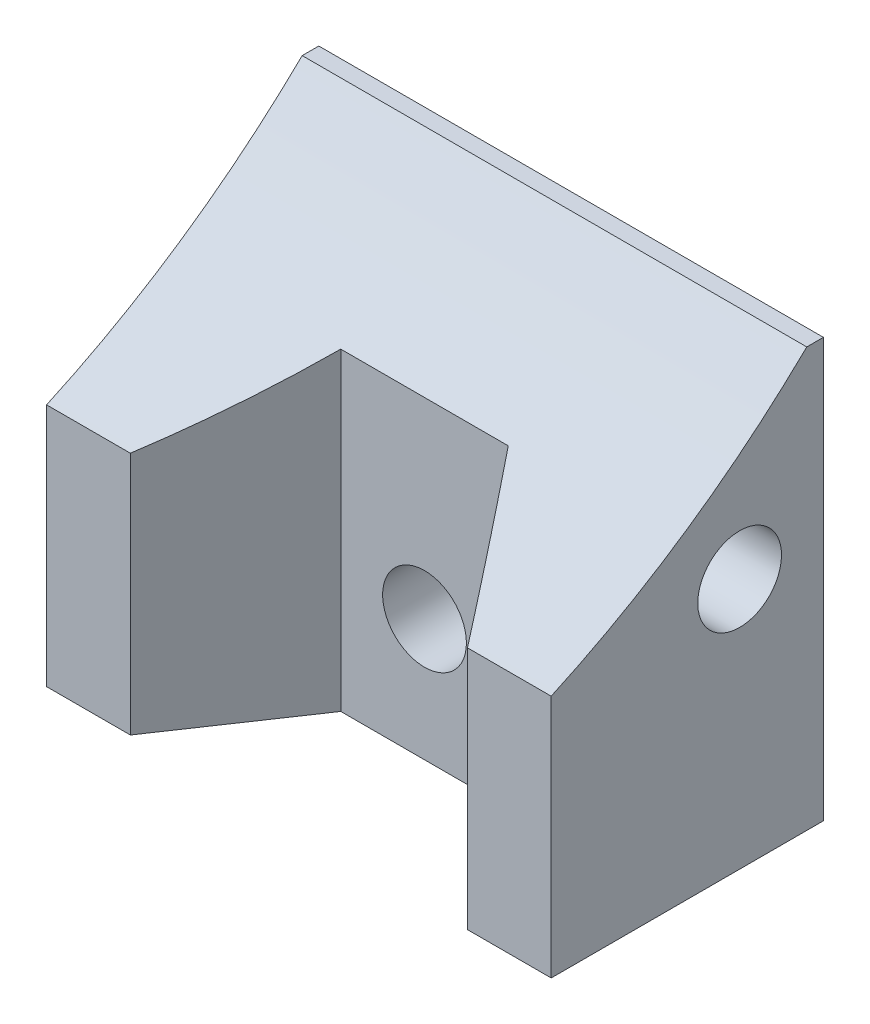
SolidWorks part; units mm, degrees
ref_plane "前视基准面" through (0, 0, 0) normal (0, 0, 1) x (1, 0, 0)
ref_plane "上视基准面" through (0, 0, 0) normal (0, 1, 0) x (1, 0, 0)
ref_plane "右视基准面" through (0, 0, 0) normal (1, 0, 0) x (0, 0, -1)
sketch "草图1" plane through (0, 0, 0) normal (0, 0, 1) x (1, 0, 0)
  line L2 (-12.05, 10) -> (12.05, 10)
  line L3 (-12.05, 10) -> (-12.05, -10)
  line L4 (-12.05, -10) -> (12.05, -10)
  line L8 (12.05, 10) -> (12.05, -10)
  line L9 (-12.05, 10) -> (12.05, -10) construction
  line L10 (-12.05, -10) -> (12.05, 10) construction
  point P0 (0, 0)
  dimension "D1" = 20
  dimension "D2" = 24.1
extrude "凸台-拉伸1" add sketch "草图1" along normal blind 13
sketch "草图3" plane through (12.05, 0, 0) normal (1, 0, 0) x (0, 0, -1)
  line L4 (0, -10) -> (0, 10)
  line L5 (0, 10) -> (-13, 10)
  line L6 (-13, 10) -> (-13, -10)
  line L7 (-13, -10) -> (0, -10)
  line L9 (-0.794, 10) -> (-13, 10)
  line L10 (-13, 10) -> (-13, 1.6572)
  arc A2 (-13, 1.6572) -> (-0.794, 10) centre (-30.8, 40.8) ccw
  point P0 (-30.8, 40.8)
  point P6 (5.5396, 51.9101)
  point P9 (12.2, 40.8)
  dimension "D1" = 0
extrude "切除-拉伸2" cut sketch "草图3" against normal through all
sketch "草图4" plane through (0, 0, 13) normal (0, 0, 1) x (1, 0, 0)
  line L0 (-12.05, -10) -> (12.05, 1.6572) construction
  line L2 (12.05, -10) -> (-12.05, 1.6572) construction
  line L3 (-12.05, 1.6572) -> (-12.05, -10) construction
  line L4 (-12.05, 1.6572) -> (12.05, 1.6572) construction
  circle A0 centre (0, -4.1714) radius 2
  dimension "D1" = 4
extrude "切除-拉伸3" cut sketch "草图4" against normal through all contours A0
sketch "草图5" plane through (0, -10, 0) normal (0, -1, 0) x (1, 0, 0)
  line L0 (0, 0) -> (0, 13) construction
  line L1 (-12.05, 0) -> (12.05, 0) construction
  line L2 (-12.05, 13) -> (12.05, 13) construction
  line L3 (-8.05, 13) -> (-4, 7)
  line L4 (-4, 7) -> (4, 7)
  line L5 (-8.05, 13) -> (8.05, 13)
  line L6 (0, 13) -> (0, 7)
  line L7 (-12.05, 13) -> (-12.05, 0) construction
  line L8 (8.05, 13) -> (4, 7)
  line M8 (12.05, 13) -> (-12.05, 13)
  dimension "D1" = 4
  dimension "D2" = 4
  dimension "D3" = 7
extrude "切除-拉伸4" cut sketch "草图5" against normal through all contours L6 L5 L3 L4 | L8 L6 L4 M8
sketch "草图6" plane through (12.05, 0, 0) normal (1, 0, 0) x (0, 0, -1)
  line L0 (-0.794, 10) -> (0, 10) construction
  line L1 (0, -10) -> (0, 10) construction
  circle A5 centre (-4, 2) radius 2
  dimension "D1" = 8
  dimension "D2" = 4
  dimension "D3" = 4
extrude "切除-拉伸5" cut sketch "草图6" against normal through all
